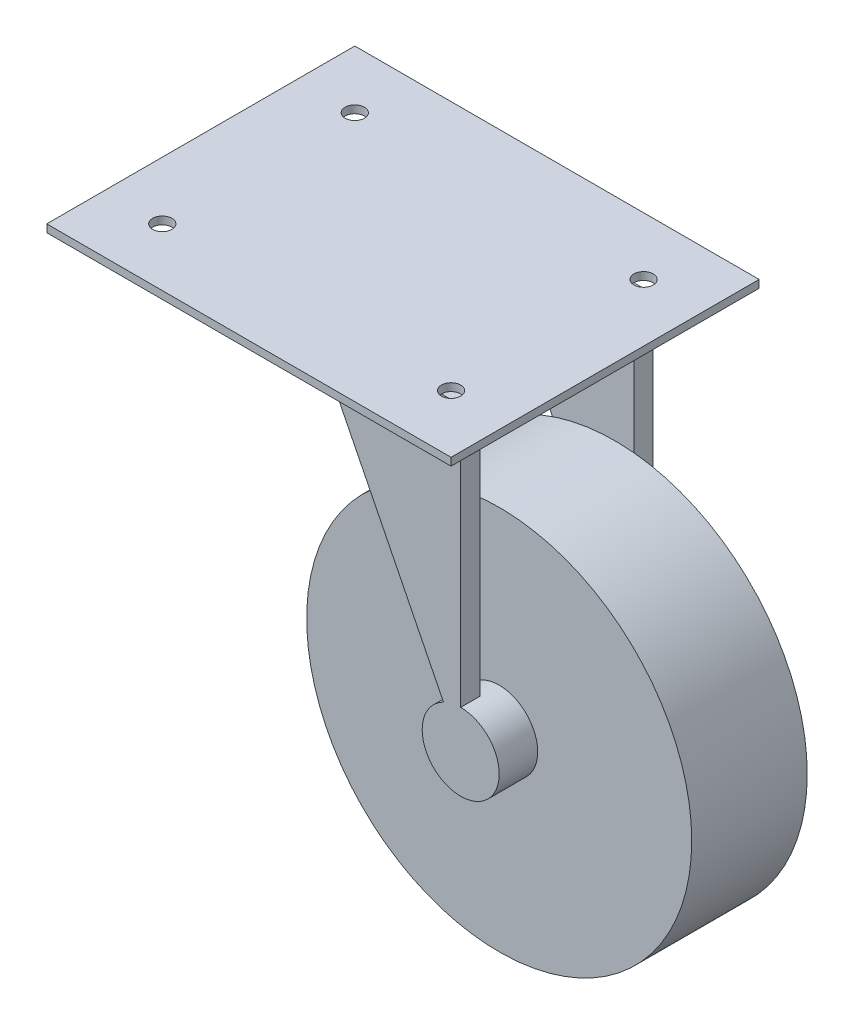
SolidWorks part; units mm, degrees
ref_plane "Piano frontale" through (0, 0, 0) normal (0, 0, 1) x (1, 0, 0)
ref_plane "Piano superiore" through (0, 0, 0) normal (0, 1, 0) x (1, 0, 0)
ref_plane "Piano destro" through (0, 0, 0) normal (1, 0, 0) x (0, 0, -1)
sketch "Schizzo1" plane through (0, 0, 0) normal (0, 0, 1) x (1, 0, 0)
  circle A0 centre (0, 0) radius 50
  dimension "D1" = 100
extrude "Estrusione-Estrusione1" add sketch "Schizzo1" along normal blind 30
sketch "Schizzo2" plane through (0, 0, 30) normal (0, 0, 1) x (1, 0, 0)
  circle A0 centre (0, 0) radius 10
  dimension "D1" = 20
extrude "Estrusione-Estrusione2" add sketch "Schizzo2" along normal blind 5
sketch "Schizzo3" plane through (0, 0, 0) normal (0, 0, -1) x (-1, 0, 0)
  circle A0 centre (0, 0) radius 10
  dimension "D1" = 20
extrude "Estrusione-Estrusione3" add sketch "Schizzo3" along normal blind 5
sketch "Schizzo4" plane through (0, 0, 35) normal (0, 0, 1) x (1, 0, 0)
  line L0 (0, 0) -> (0, 80)
  line L1 (0, 80) -> (-40, 80)
  line L2 (-40, 80) -> (0, 0)
  circle A0 centre (0, 0) radius 10
  circle M3 centre (0, 0) radius 10
  dimension "D1" = 40
  dimension "D2" = 80
extrude "Estrusione-Estrusione4" add sketch "Schizzo4" along normal blind 5 contours L1 L2 L0 M3 | L2 L0 M3 | L2 L0 M3
sketch "Schizzo5" plane through (0, 0, -5) normal (0, 0, -1) x (-1, 0, 0)
  line L0 (0, 0) -> (0, 80)
  line L1 (0, 80) -> (40, 80) construction
  line L2 (0, 10) -> (0, 80) construction
  line L3 (0, 80) -> (40, 80)
  line L4 (40, 80) -> (0, 0)
  circle A0 centre (0, 0) radius 10
  circle M3 centre (0, 0) radius 10
extrude "Estrusione-Estrusione5" add sketch "Schizzo5" along normal blind 5 contours L4 L3 L0 M3 | L4 L0 M3 | L4 L0 M3
sketch "Schizzo6" plane through (0, 80, 0) normal (0, 1, 0) x (1, 0, 0)
  line L0 (-40, -40) -> (-40, 49960) construction
  line L1 (0, -35) -> (-40, -35) construction
  line L2 (-92.5, 25) -> (12.5, 25)
  line L3 (-92.5, 25) -> (-92.5, -55)
  line L4 (-92.5, -55) -> (12.5, -55)
  line L5 (12.5, 25) -> (12.5, -55)
  line L6 (-92.5, 25) -> (12.5, -55) construction
  line L7 (-92.5, -55) -> (12.5, 25) construction
  point P3 (-40, -15)
  dimension "D1" = 105
  dimension "D2" = 80
  dimension "D3" = 20
extrude "Estrusione-Estrusione6" add sketch "Schizzo6" against normal blind 2
sketch "Schizzo7" plane through (0, 80, 0) normal (0, 1, 0) x (1, 0, 0)
  line L0 (-92.5, 10) -> (49907.5, 10) construction
  line L2 (-92.5, -40) -> (49907.5, -40) construction
  line L4 (12.5, 25) -> (-92.5, 25) construction
  line L5 (-92.5, -55) -> (12.5, -55) construction
  line L6 (-40, 25) -> (-40, -49975) construction
  line L7 (-77.5, -5.1232) -> (-77.5, -50005.1232) construction
  line L8 (-92.5, 25) -> (-92.5, -55) construction
  line L9 (-92.5, -15) -> (49907.5, -15) construction
  circle A0 centre (-77.5, -40) radius 2.5
  circle A1 centre (-2.5, -40) radius 2.5
  circle A2 centre (-2.5, 10) radius 2.5
  circle A3 centre (-77.5, 10) radius 2.5
  point P12 (-40, 25)
  point P22 (-92.5, -15)
  dimension "D3" = 5
  dimension "D1" = 15
  dimension "D2" = 15
  dimension "D4" = 15
extrude "Taglio-Estrusione1" cut sketch "Schizzo7" against normal blind 2
